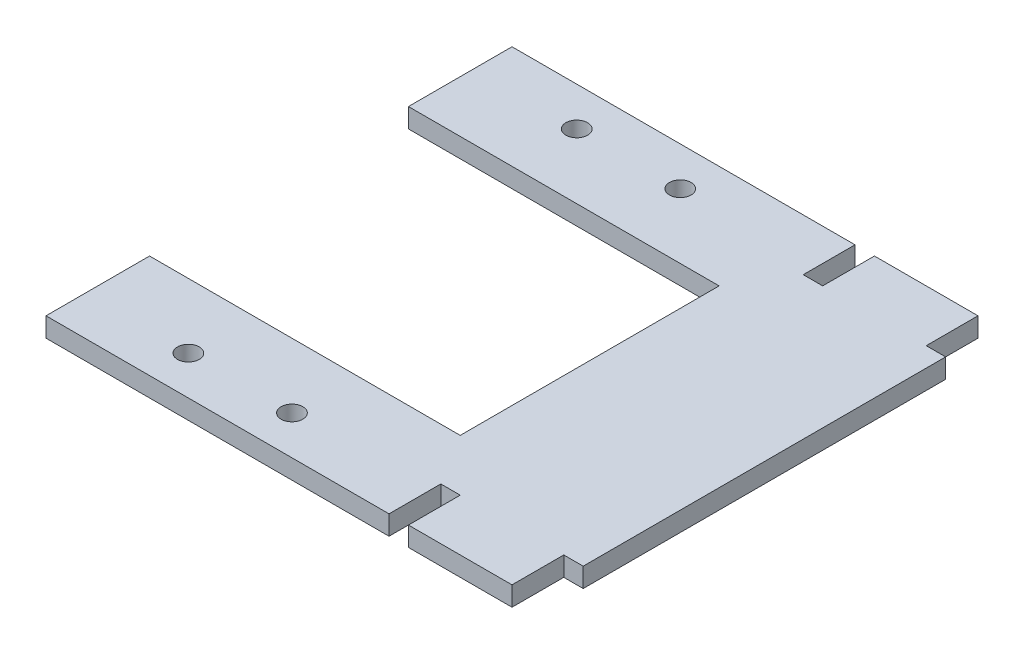
SolidWorks part; units mm, degrees
ref_plane "Front Plane" through (0, 0, 0) normal (0, 0, 1) x (1, 0, 0)
ref_plane "Top Plane" through (0, 0, 0) normal (0, 1, 0) x (1, 0, 0)
ref_plane "Right Plane" through (0, 0, 0) normal (1, 0, 0) x (0, 0, -1)
sketch "Sketch2" plane through (0, 0, 0) normal (0, 1, 0) x (1, 0, 0)
  line L0 (0, 0) -> (84.1375, 0)
  line L1 (84.1375, 0) -> (84.1375, -12.7)
  line L2 (84.1375, -12.7) -> (88.9, -12.7)
  line L3 (88.9, -12.7) -> (88.9, 0)
  line L4 (88.9, 0) -> (114.3, 0)
  line L5 (114.3, 0) -> (114.3, -12.7)
  line L6 (114.3, -12.7) -> (119.0625, -12.7)
  line L7 (119.0625, -12.7) -> (119.0625, -101.6)
  line L8 (119.0625, -101.6) -> (114.3, -101.6)
  line L9 (114.3, -101.6) -> (114.3, -114.3)
  line L10 (114.3, -114.3) -> (88.9, -114.3)
  line L11 (88.9, -114.3) -> (88.9, -101.6)
  line L12 (88.9, -101.6) -> (84.1375, -101.6)
  line L13 (84.1375, -101.6) -> (84.1375, -114.3)
  line L14 (84.1375, -114.3) -> (0, -114.3)
  line L15 (0, -114.3) -> (0, -88.9)
  line L16 (0, -88.9) -> (76.2, -88.9)
  line L17 (76.2, -88.9) -> (76.2, -25.4)
  line L18 (76.2, -25.4) -> (0, -25.4)
  line L19 (0, -25.4) -> (0, 0)
  line L20 (25.4, -9.525) -> (50.8, -9.525) construction
  line L21 (50.8, -9.525) -> (50.8, -104.775) construction
  line L22 (50.8, -104.775) -> (25.4, -104.775) construction
  line L23 (101.6, 0) -> (101.6, -114.3) construction
  circle A0 centre (50.8, -9.525) radius 2.667
  circle A1 centre (25.4, -9.525) radius 2.667
  circle A2 centre (50.8, -104.775) radius 2.667
  circle A3 centre (25.4, -104.775) radius 2.667
  dimension "D11" = 5.334
  dimension "D1" = 114.3
  dimension "D2" = 76.2
  dimension "D3" = 63.5
  dimension "D4" = 101.6
  dimension "D7" = 4.7625
  dimension "D9" = 12.7
  dimension "D10" = 25.4
  dimension "D12" = 9.525
  dimension "D13" = 9.525
  dimension "D14" = 25.4
  dimension "D15" = 50.8
extrude "Boss-Extrude1" add sketch "Sketch2" along normal blind 4.7625
